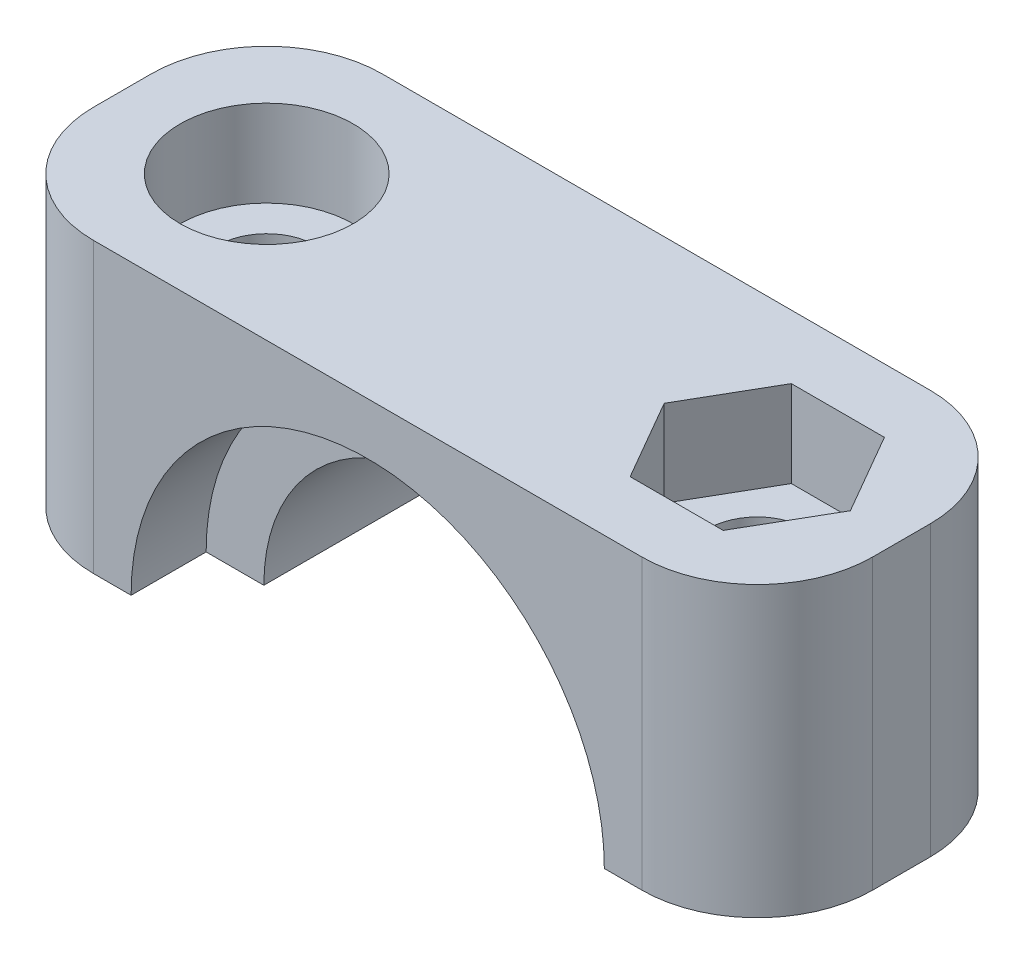
SolidWorks part; units mm, degrees
material "ABS"
ref_plane "Front Plane" through (0, 0, 0) normal (0, 0, 1) x (1, 0, 0)
ref_plane "Top Plane" through (0, 0, 0) normal (0, 1, 0) x (1, 0, 0)
ref_plane "Right Plane" through (0, 0, 0) normal (1, 0, 0) x (0, 0, -1)
sketch "Sketch1" plane through (0, 0, 0) normal (0, 0, 1) x (1, 0, 0)
  line L1 (-13.5, -5) -> (13.5, -5)
  line L2 (-13.5, -5) -> (-13.5, 5)
  line L3 (-13.5, 5) -> (13.5, 5)
  line L4 (13.5, -5) -> (13.5, 5)
  line L5 (-13.5, -5) -> (13.5, 5) construction
  line L6 (-13.5, 5) -> (13.5, -5) construction
  point P0 (0, 0)
  dimension "D1" = 10
  dimension "D2" = 27
extrude "Boss-Extrude1" add sketch "Sketch1" along normal blind 10
fillet "Fillet1" radius 4 4 edges at (13.5, 0, 0) (13.5, 0, 10) (-13.5, 0, 0) (-13.5, 0, 10)
sketch "Sketch4" plane through (0, 0, 0) normal (0, 0, -1) x (-1, 0, 0)
  line L0 (9.5, -5) -> (-9.5, -5) construction
  circle A0 centre (0, -5) radius 8.2
  dimension "D1" = 16.4
extrude "Cut-Extrude3" cut sketch "Sketch4" against normal through all
sketch "Sketch5" plane through (0, 0, 0) normal (0, 0, 1) x (1, 0, 0)
  line L0 (8.2, -5) -> (6.2, -5)
  line L1 (-6.2, -5) -> (-8.2, -5)
  arc A0 (6.2, -5) -> (-6.2, -5) centre (0, -5) ccw
  arc A1 (8.2, -5) -> (-8.2, -5) centre (0, -5) ccw construction
  arc A2 (8.2, -5) -> (-8.2, -5) centre (0, -5) ccw
  dimension "D1" = 6.2
extrude "Boss-Extrude2" add sketch "Sketch5" along normal blind 5.4 from offset 2
sketch "Sketch2" plane through (0, 5, 0) normal (0, 1, 0) x (1, 0, 0)
  line L0 (-8.5, -5) -> (8.5, -5) construction
  line L1 (0, -5) -> (0, -10) construction
  line L2 (9.5, -10) -> (-9.5, -10) construction
  line L3 (-13.5, -5) -> (-8.5, -5) construction
  line L4 (-13.5, -6) -> (-13.5, -4) construction
  circle A0 centre (-8.5, -5) radius 1.7
  circle A1 centre (8.5, -5) radius 1.7
  dimension "D1" = 17
  dimension "D2" = 3.4
extrude "Cut-Extrude1" cut sketch "Sketch2" against normal through all
sketch "Sketch3" plane through (0, 5, 0) normal (0, 1, 0) x (1, 0, 0)
  line L1 (6.8873, -7.7933) -> (10.1127, -7.7933)
  line L2 (10.1127, -7.7933) -> (11.7254, -5)
  line L3 (11.7254, -5) -> (10.1127, -2.2067)
  line L4 (10.1127, -2.2067) -> (6.8873, -2.2067)
  line L5 (6.8873, -2.2067) -> (5.2746, -5)
  line L6 (5.2746, -5) -> (6.8873, -7.7933)
  circle A0 centre (-8.5, -5) radius 3
  circle A1 centre (8.5, -5) radius 2.7933 construction
  dimension "D1" = 6
  dimension "D2" = 5.5866
extrude "Cut-Extrude2" cut sketch "Sketch3" against normal blind 3
